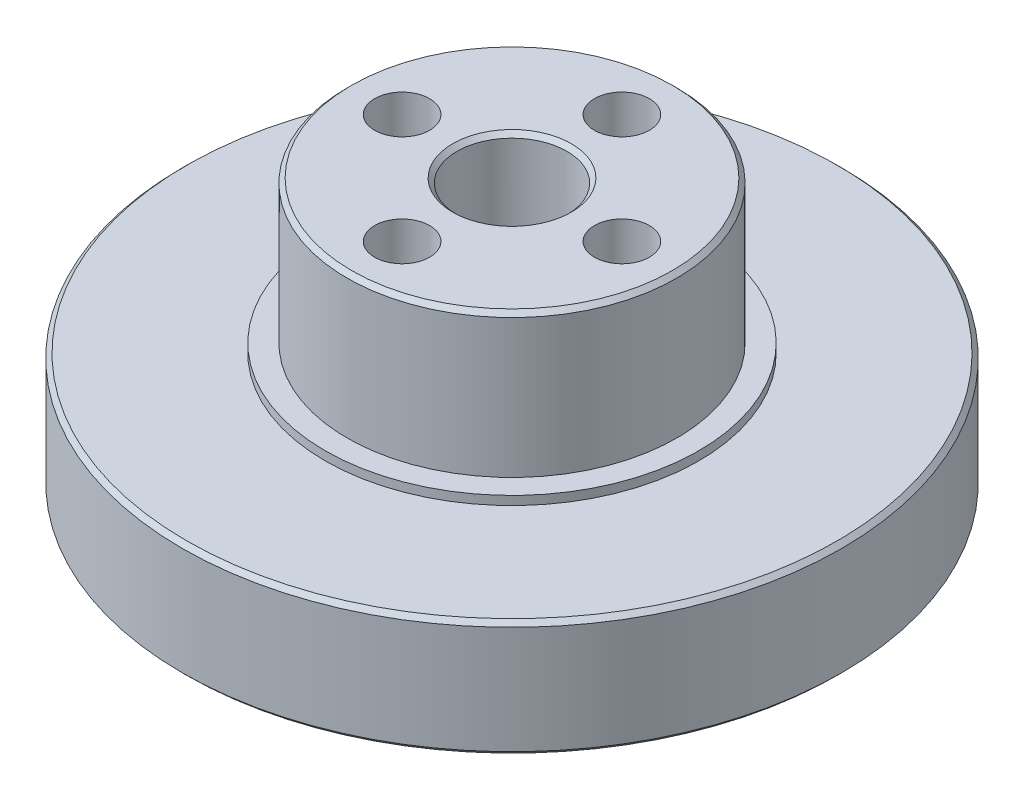
SolidWorks part; units mm, degrees
ref_plane "前视基准面" through (0, 0, 0) normal (0, 0, 1) x (1, 0, 0)
ref_plane "上视基准面" through (0, 0, 0) normal (0, 1, 0) x (1, 0, 0)
ref_plane "右视基准面" through (0, 0, 0) normal (1, 0, 0) x (0, 0, -1)
other "Configuration Table"
sketch "草图1" plane through (0, 0, 0) normal (0, 1, 0) x (1, 0, 0)
  circle A0 centre (0, 0) radius 11.525 construction
  circle A1 centre (0, 11.525) radius 1.86
  circle A2 centre (9.9809, 5.7625) radius 1.86
  circle A3 centre (9.9809, -5.7625) radius 1.86
  circle A4 centre (0, -11.525) radius 1.86
  circle A5 centre (-9.9809, -5.7625) radius 1.86
  circle A6 centre (-9.9809, 5.7625) radius 1.86
  circle A8 centre (0, 0) radius 15
  point P18 (0, 0)
  dimension "D1" = 23.05
  dimension "D2" = 3.72
  dimension "D5" = 30
  dimension "D3" = 6
extrude "凸台-拉伸1" add sketch "草图1" along normal blind 3.7
sketch "草图2" plane through (0, 3.7, 0) normal (0, 1, 0) x (1, 0, 0)
  circle A0 centre (0, 0) radius 15
extrude "凸台-拉伸2" add sketch "草图2" along normal blind 1.6
sketch "草图3" plane through (0, 5.3, 0) normal (0, 1, 0) x (1, 0, 0)
  circle A0 centre (0, 0) radius 8.5
  dimension "D1" = 17
extrude "凸台-拉伸3" add sketch "草图3" along normal blind 0.4
sketch "草图4" plane through (0, 5.7, 0) normal (0, 1, 0) x (1, 0, 0)
  circle A0 centre (0, 0) radius 7.5
  dimension "D1" = 15
extrude "凸台-拉伸4" add sketch "草图4" along normal blind 6.5
sketch "草图5" plane through (0, 12.2, 0) normal (0, 1, 0) x (1, 0, 0)
  circle A0 centre (0, 5) radius 1.25
  circle A1 centre (5, 0) radius 1.25
  circle A2 centre (0, -5) radius 1.25
  circle A3 centre (-5, 0) radius 1.25
  circle A4 centre (0, 0) radius 2.5
  point P12 (0, 0)
  dimension "D1" = 2.5
  dimension "D2" = 5
  dimension "D4" = 5
  dimension "D3" = 4
extrude "切除-拉伸1" cut sketch "草图5" against normal blind 7
chamfer "倒角1" distance 0.2 angle 45 10 edges at (-9.9809, 0, -3.9025) (-9.9809, 0, 7.6225) (0, 0, 13.385) (9.9809, 0, 7.6225) (9.9809, 0, -3.9025) (0, 0, -9.665) (0, 0, 15) (0, 12.2, 7.5) (0, 5.3, 15) (0, 12.2, 2.5)
sketch "草图7" plane through (0, 5.2, 0) normal (0, 1, 0) x (1, 0, 0)
  circle A2 centre (0, 0) radius 2.5 construction
  circle A3 centre (0, 0) radius 2.5
extrude "切除-拉伸4" cut sketch "草图7" against normal through all
sketch "草图8" plane through (0, 0, 0) normal (0, -1, 0) x (-1, 0, 0)
  circle A0 centre (0, 0) radius 6
  dimension "D1" = 6
extrude "切除-拉伸5" cut sketch "草图8" against normal blind 2
chamfer "倒角2" distance 0.5 angle 45 3 edges at (0, 0, -6) (0, 2, -2.5) (0, 2, -6)
